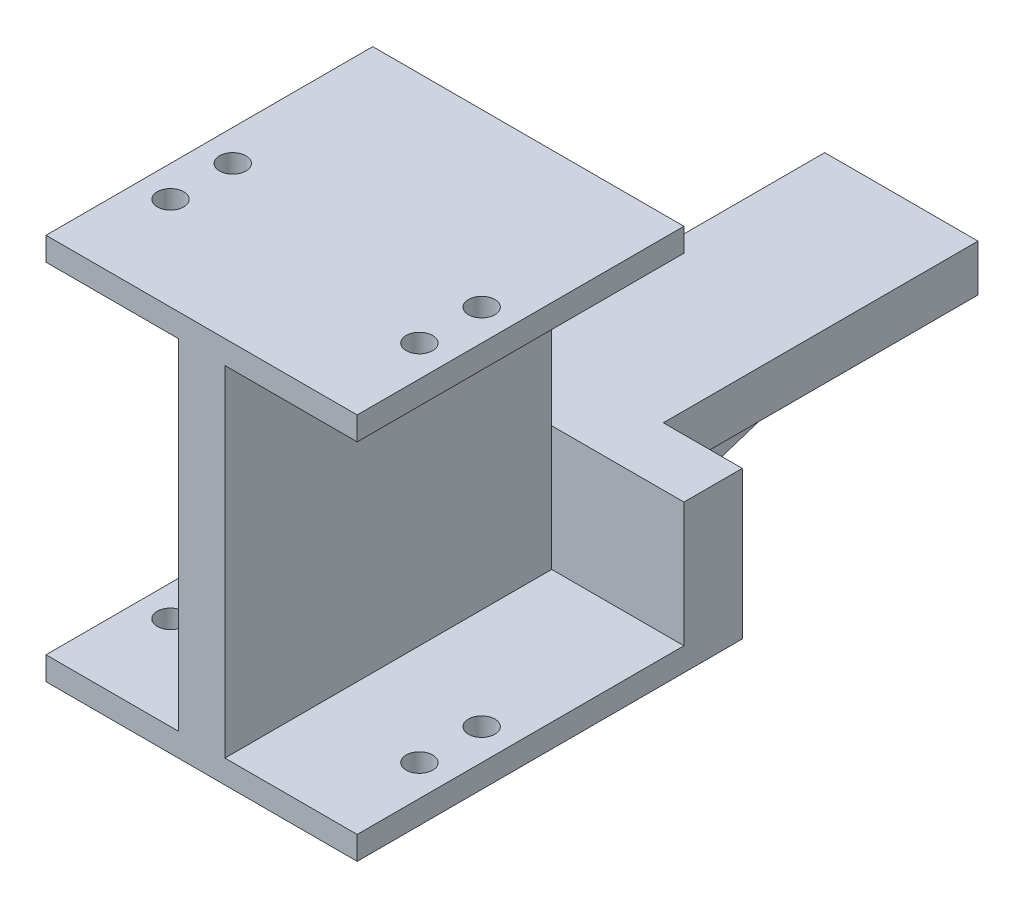
SolidWorks part; units mm, degrees
ref_plane "Front Plane" through (0, 0, 0) normal (0, 0, 1) x (1, 0, 0)
ref_plane "Top Plane" through (0, 0, 0) normal (0, 1, 0) x (1, 0, 0)
ref_plane "Right Plane" through (0, 0, 0) normal (1, 0, 0) x (0, 0, -1)
sketch "Sketch1" plane through (0, 0, 0) normal (0, 0, 1) x (1, 0, 0)
  line L0 (0, 15.35) -> (0, 24.85) construction
  line L2 (-3, -21.85) -> (-3, 21.85)
  line L4 (3, -21.85) -> (3, 21.85)
  line L5 (-3, -21.85) -> (3, 21.85) construction
  line L6 (-3, 21.85) -> (3, -21.85) construction
  line L7 (-20, 21.85) -> (-3, 21.85)
  line L8 (-20, 21.85) -> (-20, 24.85)
  line L9 (-20, 24.85) -> (20, 24.85)
  line L10 (20, 21.85) -> (20, 24.85)
  line L11 (-20, -21.85) -> (-3, -21.85)
  line L12 (-20, -21.85) -> (-20, -24.85)
  line L13 (-20, -24.85) -> (20, -24.85)
  line L14 (20, -21.85) -> (20, -24.85)
  line L15 (0, 15.35) -> (0, -15.35) construction
  line L16 (3, -21.85) -> (20, -21.85)
  line L17 (3, 21.85) -> (20, 21.85)
  point P0 (0, 0)
  point P16 (0, 0)
  dimension "D1" = 3
  dimension "D2" = 40
  dimension "D3" = 43.7
  dimension "D4" = 6
extrude "Boss-Extrude1" add sketch "Sketch1" along normal blind 42
sketch "Sketch2" plane through (0, -24.85, 0) normal (0, -1, 0) x (-1, 0, 0)
  line L1 (-20, 0) -> (20, 0)
  line L2 (-20, 0) -> (-20, 7.5)
  line L3 (-20, 7.5) -> (20, 7.5)
  line L4 (20, 0) -> (20, 7.5)
  line L6 (-10.5, 7.5) -> (10.5, 7.5) construction
  line L7 (20, -42) -> (20, 0) construction
extrude "Boss-Extrude2" add sketch "Sketch2" against normal up to surface (19 mm away)
sketch "Sketch3" plane through (0, 0, -7.5) normal (0, 0, -1) x (-1, 0, 0)
  line L0 (-20, -5.85) -> (20, -5.85) construction
  line L1 (-9.85, -5.85) -> (9.85, -5.85)
  line L2 (-9.85, -5.85) -> (-9.85, -11.85)
  line L3 (-9.85, -11.85) -> (9.85, -11.85)
  line L4 (9.85, -5.85) -> (9.85, -11.85)
  line L5 (9.85, 1.15) -> (9.85, -3.65) construction
  line L6 (-9.85, -3.65) -> (-9.85, 1.15) construction
  dimension "D1" = 6
extrude "Boss-Extrude3" add sketch "Sketch3" along normal up to vertex (40.45 mm away)
ref_plane "Plane1" through (0, 0, 0) normal (1, 0, 0) x (0, 0, -1)
sketch "Sketch4" plane through (0, 0, 0) normal (1, 0, 0) x (0, 0, -1)
  line L0 (47.95, -11.85) -> (7.5, -24.85)
rib "Rib1" sketch "Sketch4" sketch "Sketch4" thickness 6 extrusion direction parallel to sketch draft on no parameters "D1"=6
sketch "Sketch7" plane through (0, -24.85, 0) normal (0, -1, 0) x (1, 0, 0)
  line L0 (-20, 42) -> (20, 42) construction
  line L1 (20, 42) -> (20, -7.5) construction
  line L2 (0, 42) -> (0, -7.5) construction
  line L3 (3, -7.5) -> (-3, -7.5) construction
  circle A0 centre (16, 30) radius 1.7
  circle A1 centre (16, 22) radius 1.7
  circle A2 centre (-16, 22) radius 1.7
  circle A3 centre (-16, 30) radius 1.7
  dimension "D3" = 3.4
  dimension "D4" = 3.4
  dimension "D1" = 12
  dimension "D2" = 8
  dimension "D5" = 4
extrude "Cut-Extrude1" cut sketch "Sketch7" against normal through all
